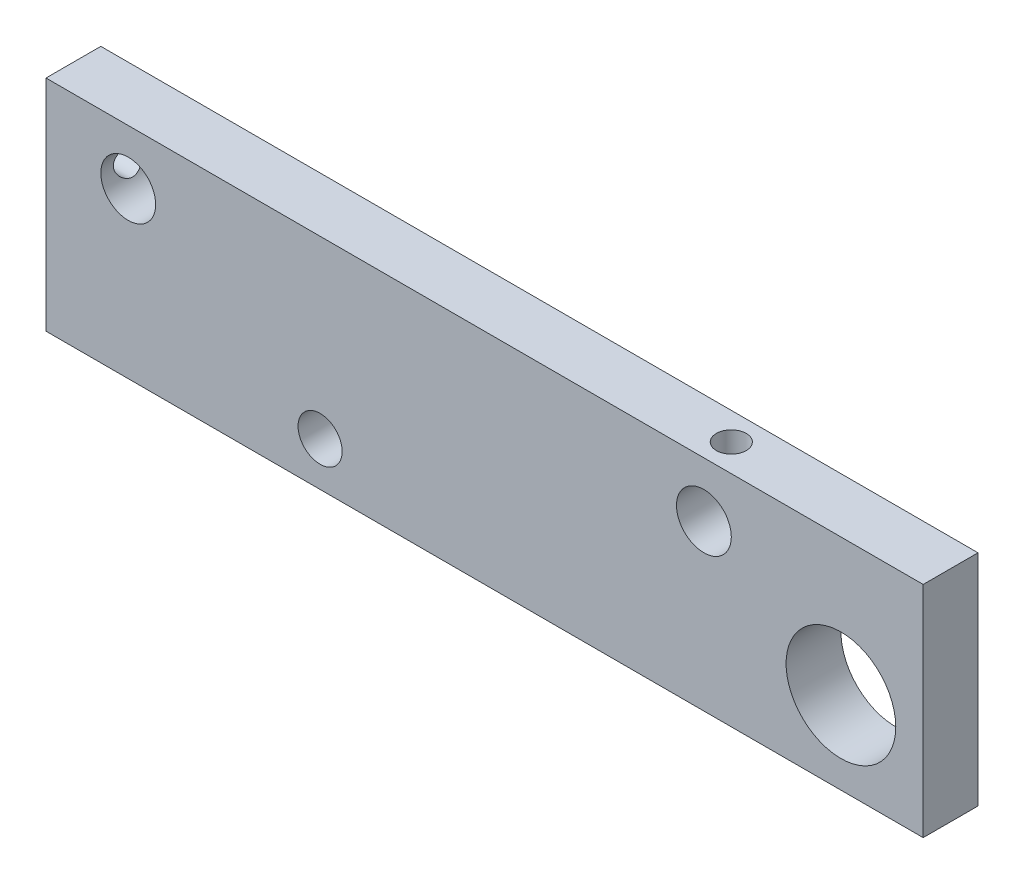
SolidWorks part; units mm, degrees
ref_plane "Front Plane" through (0, 0, 0) normal (0, 0, 1) x (1, 0, 0)
ref_plane "Top Plane" through (0, 0, 0) normal (0, 1, 0) x (1, 0, 0)
ref_plane "Right Plane" through (0, 0, 0) normal (1, 0, 0) x (0, 0, -1)
sketch "Sketch1" plane through (0, 0, 0) normal (0, 0, 1) x (1, 0, 0)
  line L1 (0, 0) -> (101.6, 0)
  line L2 (0, 0) -> (0, 25.4)
  line L3 (0, 25.4) -> (101.6, 25.4)
  line L4 (101.6, 0) -> (101.6, 25.4)
  circle A2 centre (92.075, 9.525) radius 6.35
  circle A3 centre (9.525, 19.05) radius 3.175
  circle A4 centre (9.525, 19.05) radius 14.2875 construction
  circle A5 centre (76.2, 19.05) radius 3.175
  point P11 (0, 0)
  dimension "D1" = 12.7
  dimension "D2" = 9.525
  dimension "D6" = 28.575
  dimension "D7" = 6.35
  dimension "D3" = 9.525
  dimension "D4" = 25.4
  dimension "D5" = 101.6
  dimension "D8" = 9.525
  dimension "D9" = 6.35
  dimension "D10" = 25.4
extrude "Boss-Extrude1" add sketch "Sketch1" along normal blind 6.35
hole_wizard "#8-32 Tapped Hole1" positions "3DSketch1" profile "Sketch3" tap size "#8-32" standard "ANSI Inch"
sketch3d "3DSketch1"
  line L1 (0, 25.4, 0) -> (0, 0, 0) construction
  line L2 (0, 25.4, 6.35) -> (0, 25.4, 0) construction
  line L3 (101.6, 25.4, 6.35) -> (101.6, 25.4, 0) construction
  line L4 (101.6, 25.4, 0) -> (0, 25.4, 0) construction
  point P0 (0, 19.05, 3.175)
  point P11 (76.2, 25.4, 3.175)
  dimension "D1" = 6.35
  dimension "D3" = 25.4
  dimension "D2" = 3.175
  dimension "D4" = 3.175
sketch "Sketch3" plane through (0, 19.05, 3.175) normal (0, 1, 0) x (0, 0, 1)
  line L0 (0, 0) -> (0, 6.35)
  line L1 (0, 6.35) -> (1.7272, 6.35)
  line L2 (1.7272, 6.35) -> (1.7272, 0)
  line L5 (1.7272, 0) -> (0, 0)
  line L11 (0, -6.35) -> (0, 107.95) construction
  dimension "Thru Tap Drill Dia." = 3.4544
  dimension "Thru Tap Drill Depth" = 6.35
cosmetic thread "Hole Thread1" parameters "D2"=4.1656
cosmetic thread "Hole Thread2" parameters "D2"=4.1656
hole_wizard "#8-32 Tapped Hole2" positions "3DSketch2" profile "Sketch4" tap size "#8-32" standard "ANSI Inch"
sketch3d "3DSketch2"
  line L0 (0, 0, 6.35) -> (101.6, 0, 6.35) construction
  line L1 (101.6, 0, 6.35) -> (101.6, 0, 0) construction
  line L2 (0, 0, 6.35) -> (0, 0, 0) construction
  point P0 (81.28, 0, 3.175)
  point P2 (55.88, 0, 3.175)
  point P4 (12.7, 0, 3.175)
  point P13 (68.58, 0, 3.175)
  dimension "D1" = 3.175
  dimension "D2" = 20.32
  dimension "D3" = 25.4
  dimension "D4" = 12.7
  dimension "D5" = 12.7
sketch "Sketch4" plane through (81.28, 0, 3.175) normal (1, 0, 0) x (0, 0, -1)
  line L0 (0, 0) -> (0, 11.7058)
  line L1 (0, 11.7058) -> (1.7272, 10.668)
  line L2 (1.7272, 10.668) -> (1.7272, 0)
  line L5 (1.7272, 0) -> (0, 0)
  line L10 (0, 11.7058) -> (-1.7272, 10.668) construction
  line L11 (0, -6.35) -> (0, 107.95) construction
  dimension "Tap Drill Dia." = 3.4544
  dimension "Tap Drill Depth" = 10.668
  dimension "Drill Angle" = 118
cosmetic thread "Hole Thread6" parameters "D1"=8.382, "D2"=4.1656
cosmetic thread "Hole Thread7" parameters "D1"=8.382, "D2"=4.1656
cosmetic thread "Hole Thread8" parameters "D1"=8.382, "D2"=4.1656
cosmetic thread "Hole Thread9" parameters "D1"=8.382, "D2"=4.1656
hole_wizard "1/4-20 Tapped Hole1" positions "3DSketch3" profile "Sketch5" tap size "1/4-20" standard "ANSI Inch" end condition through all
sketch3d "3DSketch3"
  line L0 (0, 0, 0) -> (101.6, 0, 0) construction
  line L1 (0, 25.4, 0) -> (0, 0, 0) construction
  point P0 (31.75, 5.08, 0)
  dimension "D1" = 5.08
  dimension "D2" = 31.75
sketch "Sketch5" plane through (31.75, 5.08, 0) normal (1, 0, 0) x (0, 1, 0)
  line L0 (0, 0) -> (0, 6.35)
  line L1 (0, 6.35) -> (2.5527, 6.35)
  line L2 (2.5527, 6.35) -> (2.5527, 0)
  line L5 (2.5527, 0) -> (0, 0)
  line L11 (0, -6.35) -> (0, 107.95) construction
  dimension "Thru Tap Drill Dia." = 5.1054
  dimension "Thru Tap Drill Depth" = 6.35
cosmetic thread "Hole Thread10" parameters "D2"=6.35
